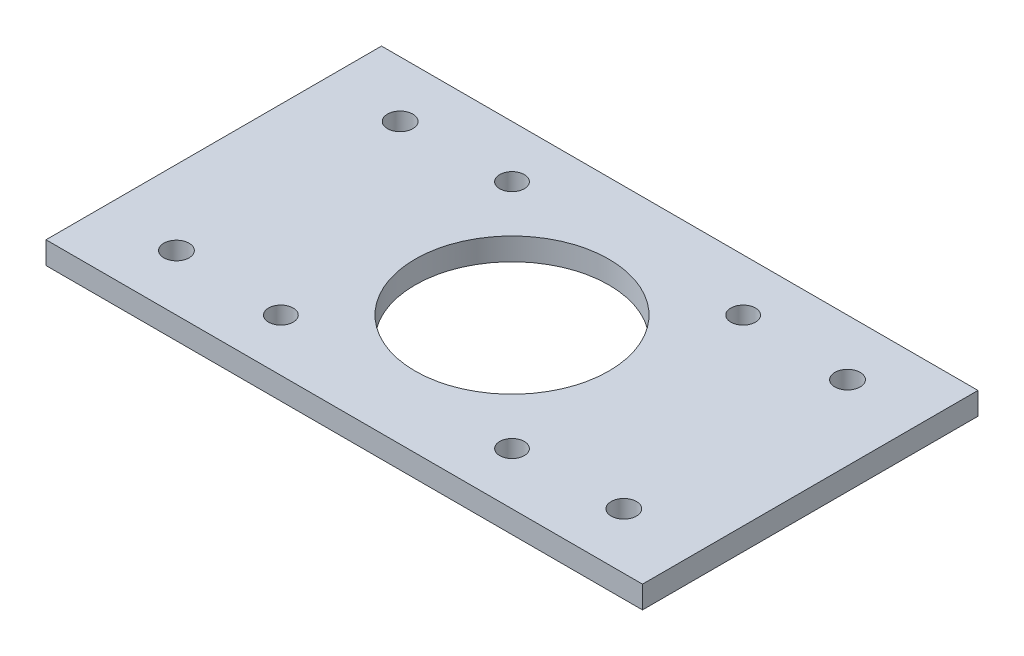
SolidWorks part; units mm, degrees
ref_plane "前视基准面" through (0, 0, 0) normal (0, 0, 1) x (1, 0, 0)
ref_plane "上视基准面" through (0, 0, 0) normal (0, 1, 0) x (1, 0, 0)
ref_plane "右视基准面" through (0, 0, 0) normal (1, 0, 0) x (0, 0, -1)
sketch "草图1" plane through (0, 0, 0) normal (0, 1, 0) x (1, 0, 0)
  line L1 (40, 22.5) -> (-40, 22.5)
  line L2 (40, 22.5) -> (40, -22.5)
  line L3 (40, -22.5) -> (-40, -22.5)
  line L4 (-40, 22.5) -> (-40, -22.5)
  line L5 (0, -22.5) -> (0, 22.5) construction
  line L6 (40, 0) -> (-40, 0) construction
  point P0 (0, 0)
  dimension "D1" = 45
  dimension "D2" = 80
extrude "凸台-拉伸1" add sketch "草图1" along normal blind 3
sketch "草图2" plane through (0, 3, 0) normal (0, 1, 0) x (1, 0, 0)
  line L1 (15.5, 15.5) -> (-15.5, 15.5) construction
  line L2 (15.5, 15.5) -> (15.5, -15.5) construction
  line L3 (15.5, -15.5) -> (-15.5, -15.5) construction
  line L4 (-15.5, 15.5) -> (-15.5, -15.5) construction
  line L5 (0, -15.5) -> (0, 15.5) construction
  line L6 (15.5, 0) -> (-15.5, 0) construction
  circle A0 centre (-15.5, 15.5) radius 1.65
  circle A1 centre (15.5, 15.5) radius 1.65
  circle A2 centre (-15.5, -15.5) radius 1.65
  circle A3 centre (15.5, -15.5) radius 1.65
  point P0 (0, 0)
  dimension "D2" = 3.3
  dimension "D3" = 3.3
  dimension "D4" = 3.3
  dimension "D5" = 3.3
  dimension "D1" = 31
extrude "切除-拉伸1" cut sketch "草图2" against normal blind 3
sketch "草图3" plane through (0, 3, 0) normal (0, 1, 0) x (1, 0, 0)
  circle A0 centre (0, 0) radius 13
  dimension "D1" = 26
extrude "切除-拉伸2" cut sketch "草图3" against normal blind 10
sketch "草图5" plane through (0, 3, 0) normal (0, 1, 0) x (1, 0, 0)
  line L0 (0, 0) -> (-32.9671, 0) construction
  line L1 (0, 0) -> (0, 25.7719) construction
  circle A0 centre (-30, 15) radius 1.7
  circle A1 centre (30, 15) radius 1.7
  circle A2 centre (-30, -15) radius 1.7
  circle A3 centre (30, -15) radius 1.7
  dimension "D1" = 3.4
  dimension "D2" = 15
  dimension "D3" = 30
extrude "切除-拉伸4" cut sketch "草图5" against normal blind 10
